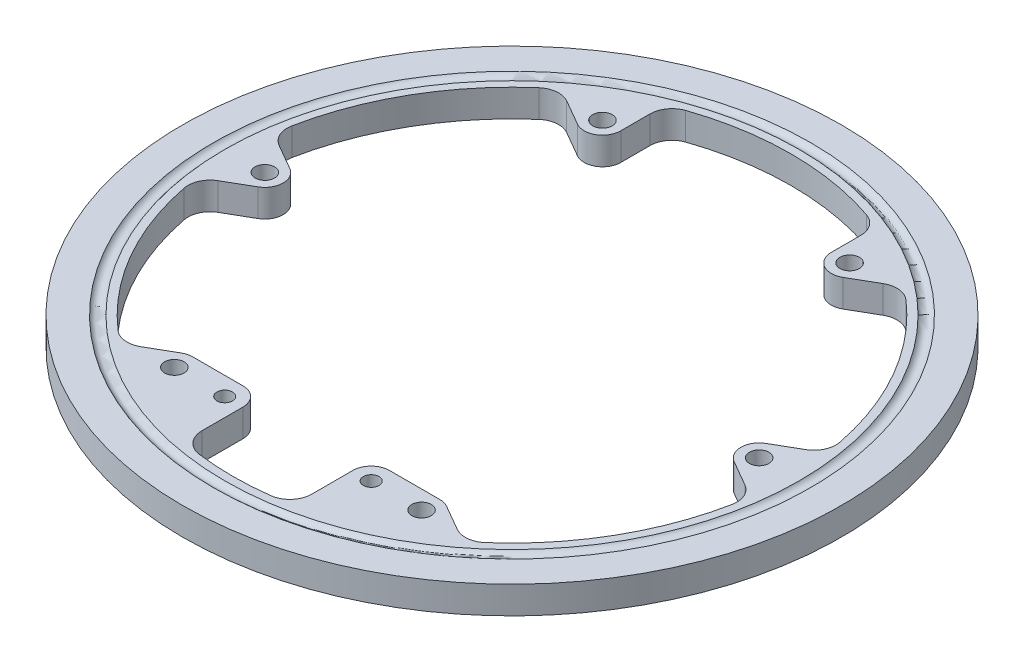
SolidWorks part; units mm, degrees
ref_plane "Front Plane" through (0, 0, 0) normal (0, 0, 1) x (1, 0, 0)
ref_plane "Top Plane" through (0, 0, 0) normal (0, 1, 0) x (1, 0, 0)
ref_plane "Right Plane" through (0, 0, 0) normal (1, 0, 0) x (0, 0, -1)
sketch "Sketch1" plane through (0, 0, 0) normal (0, 1, 0) x (1, 0, 0)
  line L8 (0, 0) -> (-51.7328, 0) construction
  circle A0 centre (0, 0) radius 114.3
  circle A1 centre (0, 0) radius 96.8375
  dimension "D1" = 228.6
  dimension "D2" = 193.675
extrude "Boss-Extrude1" add sketch "Sketch1" along normal blind 9.525
sketch "Sketch3" plane through (0, 0, 0) normal (0, -1, 0) x (1, 0, 0)
  line L0 (0, 0) -> (96.8375, 0) construction
  line L1 (95.9303, -13.2244) -> (82.55, -5.4993)
  line L2 (82.55, 5.4993) -> (95.9303, 13.2244)
  circle A0 centre (0, 0) radius 96.8375 construction
  arc A1 (95.9303, -13.2244) -> (95.9303, 13.2244) centre (0, 0) ccw
  arc A2 (82.55, -5.4993) -> (82.55, 5.4993) centre (85.725, 0) cw
  dimension "D1" = 6.35
  dimension "D2" = 60
  dimension "D3" = 85.725
extrude "Boss-Extrude2" add sketch "Sketch3" against normal up to surface (9.525 mm away) up to face at (0, 9.525, 114.3)
fillet "Fillet2" radius 7.62 2 edges at (95.9303, 4.7625, 13.2244) (95.9303, 4.7625, -13.2244)
pattern_circular "CirPattern1" count 6 over 360 about axis through (0, 0, 0) along (0, 1, 0) of "Boss-Extrude2", "Fillet2"
sketch "Sketch7" plane through (0, 9.525, 0) normal (0, 1, 0) x (1, 0, 0)
  line L0 (0, 0) -> (0, -74.24) construction
  line L1 (0, -74.24) -> (25.4, -74.24) construction
  line L2 (0, -74.24) -> (-25.4, -74.24) construction
  line L3 (42.8625, -67.89) -> (25.4, -67.89)
  line L4 (-42.8625, -67.89) -> (-25.4, -67.89)
  line L5 (19.05, -74.24) -> (19.05, -94.9452)
  line L6 (-19.05, -94.9452) -> (-19.05, -74.24)
  line L7 (36.5125, -84.4096) -> (36.5125, -74.24) construction
  line L8 (-36.5125, -74.24) -> (-36.5125, -84.4096) construction
  line L9 (-36.5125, -74.24) -> (-36.5125, -84.4096)
  line L10 (36.5125, -84.4096) -> (36.5125, -74.24)
  arc A0 (25.4, -67.89) -> (19.05, -74.24) centre (25.4, -74.24) ccw
  arc A1 (-19.05, -74.24) -> (-25.4, -67.89) centre (-25.4, -74.24) ccw
  arc A2 (-36.5125, -74.24) -> (-46.0375, -68.7408) centre (-42.8625, -74.24) ccw construction
  arc A3 (46.0375, -68.7408) -> (36.5125, -74.24) centre (42.8625, -74.24) ccw construction
  arc A4 (-31.3602, -91.619) -> (31.3602, -91.619) centre (0, 0) ccw construction
  arc A5 (19.05, -74.24) -> (25.4, -67.89) centre (25.4, -74.24) ccw construction
  arc A6 (-25.4, -67.89) -> (-19.05, -74.24) centre (-25.4, -74.24) ccw construction
  arc A7 (31.3602, -91.619) -> (36.5125, -84.4096) centre (28.8925, -84.4096) ccw construction
  arc A9 (-36.5125, -84.4096) -> (-31.3602, -91.619) centre (-28.8925, -84.4096) ccw construction
  arc A10 (-36.5125, -84.4096) -> (-31.3602, -91.619) centre (-28.8925, -84.4096) ccw
  arc A11 (-36.5125, -74.24) -> (-42.8625, -67.89) centre (-42.8625, -74.24) ccw
  arc A12 (-31.3602, -91.619) -> (-19.05, -94.9452) centre (0, 0) ccw
  arc A13 (31.3602, -91.619) -> (36.5125, -84.4096) centre (28.8925, -84.4096) ccw
  arc A14 (42.8625, -67.89) -> (36.5125, -74.24) centre (42.8625, -74.24) ccw
  arc A15 (19.05, -94.9452) -> (31.3602, -91.619) centre (0, 0) ccw
  dimension "D1" = 50.8
  dimension "D3" = 20.7052
sketch "Sketch4" plane through (0, 0, 0) normal (0, -1, 0) x (-1, 0, 0)
  point P0 (-42.8625, 74.24)
  point P3 (42.8625, 74.24)
  point P6 (85.725, 0)
  point P9 (42.8625, -74.24)
  point P12 (-42.8625, -74.24)
  point P15 (-85.725, 0)
hole_wizard "1/4 Clearance Hole1" positions "Sketch4" profile "Sketch6" hole size "1/4" standard "ANSI Inch" end condition through all
sketch "Sketch6" plane through (42.8625, 0, -74.24) normal (1, 0, 0) x (0, 0, -1)
  line L0 (0, 0) -> (0, 9.525)
  line L1 (0, 9.525) -> (3.3782, 9.525)
  line L2 (3.3782, 9.525) -> (3.3782, 0)
  line L5 (3.3782, 0) -> (0, 0)
  line L11 (0, -6.35) -> (0, 107.95) construction
  dimension "Thru Hole Dia." = 6.7564
  dimension "Thru Hole Depth" = 9.525
sketch "Sketch2" plane through (0, 0, 0) normal (1, 0, 0) x (0, 0, -1)
  line L0 (-114.3, 4.7625) -> (-68.0352, 4.7625) construction
  line L1 (-114.3, 9.525) -> (-114.3, 0) construction
  line L2 (-114.3, 0) -> (114.3, 0) construction
  line L3 (0, 0) -> (0, 24.7794) construction
  circle A0 centre (-101.6, 10.795) radius 2.3813
  circle A1 centre (-101.6, -1.27) radius 2.3813
  dimension "D3" = 4.7625
  dimension "D1" = 12.065
  dimension "D2" = 1.27
  dimension "D4" = 203.2
revolve "Cut-Revolve1" cut sketch "Sketch2" angle 360 about L3
extrude "Boss-Extrude3" add sketch "Sketch7" against normal up to surface (9.525 mm away) up to face at (85.725, 0, -3.3782)
fillet "Fillet3" radius 7.62 2 edges at (-19.05, 4.7625, 94.9452) (19.05, 4.7625, 94.9452)
sketch "Sketch8" plane through (0, 9.525, 0) normal (0, 1, 0) x (1, 0, 0)
  point P0 (25.4, -74.24)
  point P3 (-25.4, -74.24)
hole_wizard "1/4-28 Tapped Hole1" positions "Sketch8" profile "Sketch9" tap size "1/4-28" standard "ANSI Inch" end condition through all
sketch "Sketch9" plane through (25.4, 9.525, 74.24) normal (1, 0, 0) x (0, 0, 1)
  line L0 (0, 0) -> (0, 9.525)
  line L1 (0, 9.525) -> (2.7051, 9.525)
  line L2 (2.7051, 9.525) -> (2.7051, 0)
  line L5 (2.7051, 0) -> (0, 0)
  line L11 (0, -6.35) -> (0, 107.95) construction
  dimension "Thru Tap Drill Dia." = 5.4102
  dimension "Thru Tap Drill Depth" = 9.525
